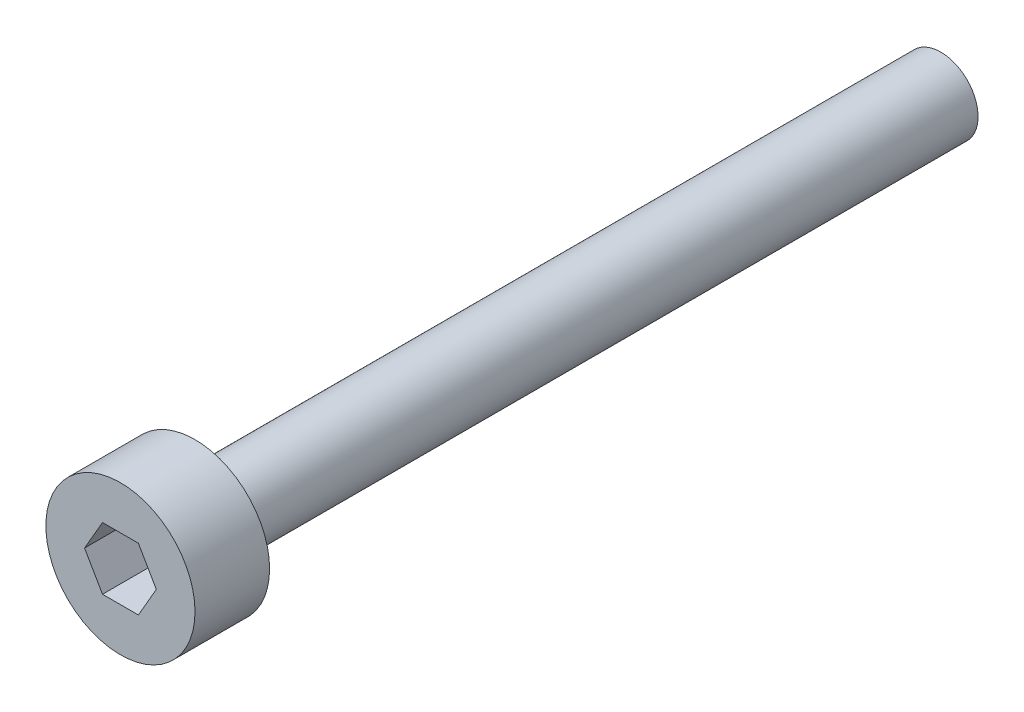
SolidWorks part; units mm, degrees
ref_plane "正面" through (0, 0, 0) normal (0, 0, 1) x (1, 0, 0)
ref_plane "平面" through (0, 0, 0) normal (0, 1, 0) x (1, 0, 0)
ref_plane "右側面" through (0, 0, 0) normal (1, 0, 0) x (0, 0, -1)
sketch "ｽｹｯﾁ5" plane through (0, 0, 0) normal (0, 0, 1) x (1, 0, 0)
  circle A0 centre (0, 0) radius 3
  dimension "D1" = 6
extrude "ﾎﾞｽ - 押し出し1" add sketch "ｽｹｯﾁ5" along normal blind 3
sketch "ｽｹｯﾁ6" plane through (0, 0, 3) normal (0, 0, 1) x (1, 0, 0)
  line L1 (1.4434, 0) -> (0.7217, 1.25)
  line L2 (0.7217, 1.25) -> (-0.7217, 1.25)
  line L3 (-0.7217, 1.25) -> (-1.4434, 0)
  line L4 (-1.4434, 0) -> (-0.7217, -1.25)
  line L5 (-0.7217, -1.25) -> (0.7217, -1.25)
  line L6 (0.7217, -1.25) -> (1.4434, 0)
  circle A0 centre (0, 0) radius 1.25 construction
  dimension "D1" = 2.5
extrude "ｶｯﾄ - 押し出し1" cut sketch "ｽｹｯﾁ6" against normal blind 2
sketch "ｽｹｯﾁ7" plane through (0, 0, 0) normal (0, 0, -1) x (-1, 0, 0)
  circle A0 centre (0, 0) radius 1.5
  dimension "D1" = 3
extrude "ﾎﾞｽ - 押し出し2" add sketch "ｽｹｯﾁ7" along normal blind 30
